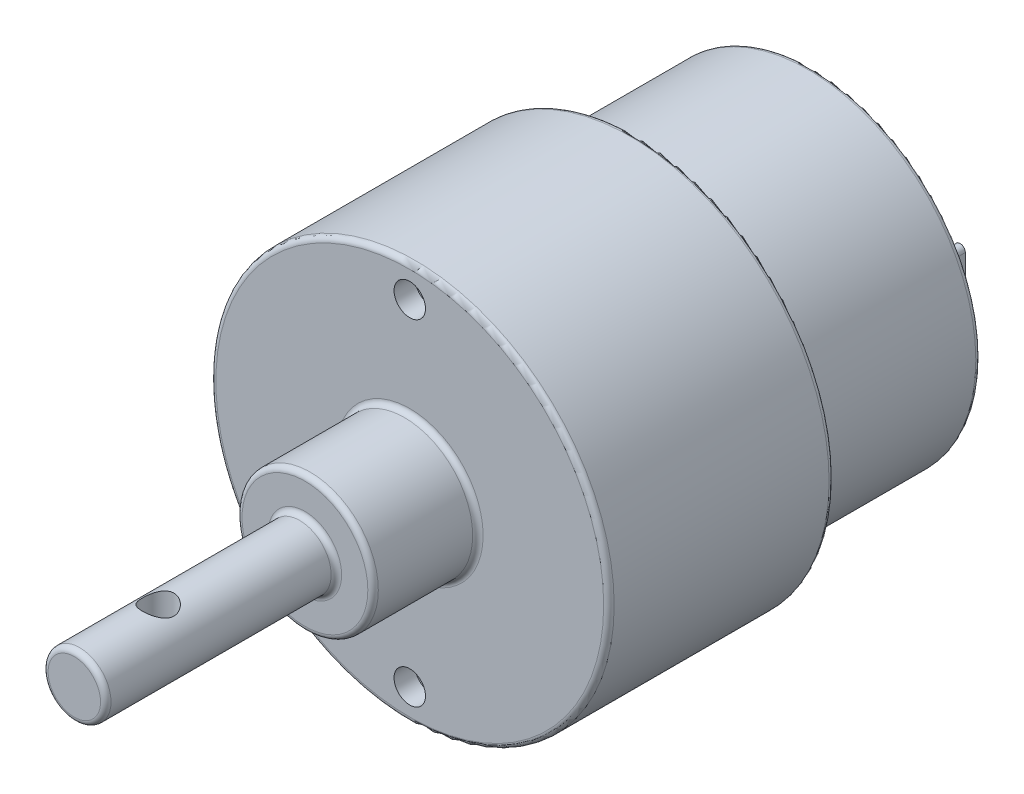
SolidWorks part; units mm, degrees
ref_plane "Front Plane" through (0, 0, 0) normal (0, 0, 1) x (1, 0, 0)
ref_plane "Top Plane" through (0, 0, 0) normal (0, 1, 0) x (1, 0, 0)
ref_plane "Right Plane" through (0, 0, 0) normal (1, 0, 0) x (0, 0, -1)
sketch "Sketch2" plane through (0, 0, 0) normal (1, 0, 0) x (0, 0, -1)
  line L0 (-60.1463, 0) -> (53.2683, 0) construction
  line L1 (-53.561, 0) -> (-53.561, 2.5)
  line L2 (-53.061, 3) -> (-32.061, 3)
  line L3 (-31.561, 3.5) -> (-31.561, 6)
  line L4 (-31.061, 6.5) -> (-22.061, 6.5)
  line L5 (-21.561, 7) -> (-21.561, 18.5)
  line L6 (-21.061, 19) -> (-0.561, 19)
  line L7 (-0.061, 18.5) -> (-0.061, 16.5)
  line L8 (0.439, 16) -> (16.439, 16)
  line L9 (16.939, 15.5) -> (16.939, 0)
  line L10 (-53.561, 0) -> (16.939, 0)
  arc A0 (-0.061, 16.5) -> (0.439, 16) centre (0.439, 16.5) ccw
  arc A1 (-22.061, 6.5) -> (-21.561, 7) centre (-22.061, 7) ccw
  arc A2 (-32.061, 3) -> (-31.561, 3.5) centre (-32.061, 3.5) ccw
  arc A3 (16.439, 16) -> (16.939, 15.5) centre (16.439, 15.5) cw
  arc A4 (-0.561, 19) -> (-0.061, 18.5) centre (-0.561, 18.5) cw
  arc A5 (-21.561, 18.5) -> (-21.061, 19) centre (-21.061, 18.5) cw
  arc A6 (-31.561, 6) -> (-31.061, 6.5) centre (-31.061, 6) cw
  arc A7 (-53.561, 2.5) -> (-53.061, 3) centre (-53.061, 2.5) cw
  point P15 (-0.061, 16)
  point P18 (-21.561, 6.5)
  point P21 (-31.561, 3)
  point P24 (16.939, 16)
  point P27 (-0.061, 19)
  point P30 (-21.561, 19)
  point P33 (-31.561, 6.5)
  point P36 (-53.561, 3)
  dimension "D9" = 0.5
  dimension "D1" = 3
  dimension "D2" = 6.5
  dimension "D3" = 19
  dimension "D4" = 16
  dimension "D5" = 22
  dimension "D6" = 10
  dimension "D7" = 21.5
  dimension "D8" = 17
revolve "Revolve1" add sketch "Sketch2" angle 360 about L0
sketch "Sketch3" plane through (0, 0, 0) normal (0, 1, 0) x (1, 0, 0)
  line L0 (-2.5, -53.561) -> (2.5, -53.561) construction
  circle A0 centre (0, -45.561) radius 1.5
  dimension "D1" = 8
extrude "Cut-Extrude1" cut sketch "Sketch3" against normal mid plane 10
sketch "Sketch4" plane through (0, 0, -16.939) normal (0, 0, -1) x (-1, 0, 0)
  line L0 (-8, 1.8846) -> (-8, -1.423) construction
  line L1 (-7.5, 1.8846) -> (-7.5, -1.423)
  line L2 (-8.5, 1.8846) -> (-8.5, -1.423)
  line L3 (8, 1.8846) -> (8, -1.423) construction
  line L4 (8.5, 1.8846) -> (8.5, -1.423)
  line L5 (7.5, 1.8846) -> (7.5, -1.423)
  arc A0 (-7.5, 1.8846) -> (-8.5, 1.8846) centre (-8, 1.8846) ccw
  arc A1 (-8.5, -1.423) -> (-7.5, -1.423) centre (-8, -1.423) ccw
  arc A2 (8.5, 1.8846) -> (7.5, 1.8846) centre (8, 1.8846) ccw
  arc A3 (7.5, -1.423) -> (8.5, -1.423) centre (8, -1.423) ccw
  point P2 (-8, 0.2308)
  point P7 (8, 0.2308)
  dimension "D1" = 0.5
  dimension "D2" = 0.5
  dimension "D3" = 8
  dimension "D4" = 8
extrude "Boss-Extrude1" add sketch "Sketch4" along normal blind 6
sketch "Sketch5" plane through (0, 0, 21.561) normal (0, 0, 1) x (1, 0, 0)
  circle A0 centre (0, 16) radius 1.5
  circle A1 centre (0, -16) radius 1.5
  dimension "D1" = 3
  dimension "D2" = 3
  dimension "D4" = 16
  dimension "D3" = 32
extrude "Cut-Extrude2" cut sketch "Sketch5" against normal blind 2
